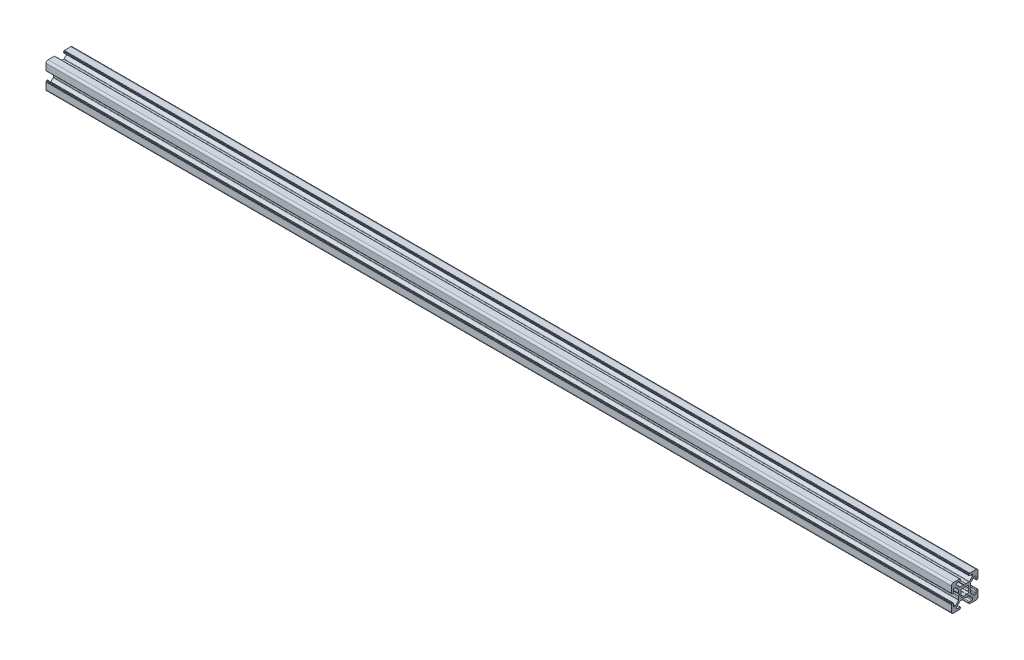
SolidWorks part; units mm, degrees
ref_plane "Front Plane" through (0, 0, 0) normal (0, 0, 1) x (1, 0, 0)
ref_plane "Top Plane" through (0, 0, 0) normal (0, 1, 0) x (1, 0, 0)
ref_plane "Right Plane" through (0, 0, 0) normal (1, 0, 0) x (0, 0, -1)
sketch "Sketch1" plane through (0, 0, 0) normal (0, 0, 1) x (1, 0, 0)
  line L0 (0, 0) -> (680, 0)
  dimension "D1" = 680
other "Metric 2020(1)"
ref_plane "Plane1" through (0, 0, 0) normal (1, 0, 0) x (0, 1, 0)
sketch "Sketch11" plane through (0, 0, 0) normal (1, 0, 0) x (0, 1, 0)
  line L0 (0, 10) -> (0, -10) construction
  line L1 (-10, 0) -> (10, 0) construction
  line L2 (-3.5, 8.5) -> (-5.5, 8.5)
  line L3 (-3.55, 9.7) -> (-3.55, 9.8)
  line L4 (-6, 7.2678) -> (-6, 8)
  line L5 (-7.2678, 6) -> (-8, 6)
  line L6 (-3.75, 10) -> (-8.5, 10)
  line L7 (-9.7, 3.55) -> (-9.8, 3.55)
  line L8 (-9.5, 3.2) -> (-9.5, 3.35)
  line L9 (-9, 3) -> (-9.3, 3)
  line L10 (-4.4732, 0.8536) -> (-4.0381, 0.1)
  line L11 (-4.5, 3.2322) -> (-4.5, 0.9536)
  line L12 (-8.5, 3.5) -> (-8.5, 5.5)
  line L13 (-10, 3.75) -> (-10, 8.5)
  line L14 (-3.5858, 4.6464) -> (-5.8536, 6.9142)
  line L15 (-4.6464, 3.5858) -> (-6.9142, 5.8536)
  line L16 (-3.2, 9.5) -> (-3.35, 9.5)
  line L17 (-3, 9) -> (-3, 9.3)
  line L18 (-0.8536, 4.4732) -> (-0.1, 4.0381)
  line L19 (-3.2322, 4.5) -> (-0.9536, 4.5)
  line L20 (-1.2582, 2.4453) -> (-1.9139, 2.9896)
  line L21 (-2.4453, 1.2582) -> (-2.9922, 1.9099)
  line L22 (3.5, -8.5) -> (5.5, -8.5)
  line L23 (3.55, -9.7) -> (3.55, -9.8)
  line L24 (6, -7.2678) -> (6, -8)
  line L25 (7.2678, -6) -> (8, -6)
  line L26 (3.75, -10) -> (8.5, -10)
  line L27 (9.7, -3.55) -> (9.8, -3.55)
  line L28 (9.5, -3.2) -> (9.5, -3.35)
  line L29 (9, -3) -> (9.3, -3)
  line L30 (4.4732, -0.8536) -> (4.0381, -0.1)
  line L31 (4.5, -3.2322) -> (4.5, -0.9536)
  line L32 (8.5, -3.5) -> (8.5, -5.5)
  line L33 (10, -3.75) -> (10, -8.5)
  line L34 (3.5858, -4.6464) -> (5.8536, -6.9142)
  line L35 (4.6464, -3.5858) -> (6.9142, -5.8536)
  line L36 (3.2, -9.5) -> (3.35, -9.5)
  line L37 (3, -9) -> (3, -9.3)
  line L38 (0.8536, -4.4732) -> (0.1, -4.0381)
  line L39 (3.2322, -4.5) -> (0.9536, -4.5)
  line L40 (1.2582, -2.4453) -> (1.9139, -2.9896)
  line L41 (2.4453, -1.2582) -> (2.9922, -1.9099)
  line L42 (-2.4453, -1.2582) -> (-2.9922, -1.9099)
  line L43 (-1.2582, -2.4453) -> (-1.9139, -2.9896)
  line L44 (-3.2322, -4.5) -> (-0.9536, -4.5)
  line L45 (-0.8536, -4.4732) -> (-0.1, -4.0381)
  line L46 (-3, -9) -> (-3, -9.3)
  line L47 (-3.2, -9.5) -> (-3.35, -9.5)
  line L48 (-4.6464, -3.5858) -> (-6.9142, -5.8536)
  line L49 (-3.5858, -4.6464) -> (-5.8536, -6.9142)
  line L50 (-10, -3.75) -> (-10, -8.5)
  line L51 (-8.5, -3.5) -> (-8.5, -5.5)
  line L52 (-4.5, -3.2322) -> (-4.5, -0.9536)
  line L53 (-4.4732, -0.8536) -> (-4.0381, -0.1)
  line L54 (-9, -3) -> (-9.3, -3)
  line L55 (-9.5, -3.2) -> (-9.5, -3.35)
  line L56 (-9.7, -3.55) -> (-9.8, -3.55)
  line L57 (2.4453, 1.2582) -> (2.9922, 1.9099)
  line L58 (1.2582, 2.4453) -> (1.9139, 2.9896)
  line L59 (3.2322, 4.5) -> (0.9536, 4.5)
  line L60 (0.8536, 4.4732) -> (0.1, 4.0381)
  line L61 (-3.75, -10) -> (-8.5, -10)
  line L62 (-7.2678, -6) -> (-8, -6)
  line L63 (-6, -7.2678) -> (-6, -8)
  line L64 (3, 9) -> (3, 9.3)
  line L65 (3.2, 9.5) -> (3.35, 9.5)
  line L66 (4.6464, 3.5858) -> (6.9142, 5.8536)
  line L67 (3.5858, 4.6464) -> (5.8536, 6.9142)
  line L68 (10, 3.75) -> (10, 8.5)
  line L69 (8.5, 3.5) -> (8.5, 5.5)
  line L70 (4.5, 3.2322) -> (4.5, 0.9536)
  line L71 (4.4732, 0.8536) -> (4.0381, 0.1)
  line L72 (9, 3) -> (9.3, 3)
  line L73 (9.5, 3.2) -> (9.5, 3.35)
  line L74 (9.7, 3.55) -> (9.8, 3.55)
  line L75 (3.75, 10) -> (8.5, 10)
  line L76 (7.2678, 6) -> (8, 6)
  line L77 (6, 7.2678) -> (6, 8)
  line L78 (3.55, 9.7) -> (3.55, 9.8)
  line L79 (3.5, 8.5) -> (5.5, 8.5)
  line L80 (-3.55, -9.7) -> (-3.55, -9.8)
  line L81 (-3.5, -8.5) -> (-5.5, -8.5)
  line L83 (10, -10) -> (-10, -10) construction
  line L84 (10, -10) -> (10, 10) construction
  line L85 (10, 10) -> (-10, 10) construction
  line L86 (-10, -10) -> (-10, 10) construction
  line L87 (10, -10) -> (-10, 10) construction
  line L88 (10, 10) -> (-10, -10) construction
  arc A0 (-10, 8.5) -> (-8.5, 10) centre (-8.5, 8.5) cw
  arc A1 (-8.5, 5.5) -> (-8, 6) centre (-8, 5.5) cw
  arc A2 (-7.2678, 6) -> (-6.9142, 5.8536) centre (-7.2678, 5.5) cw
  arc A3 (-5.8536, 6.9142) -> (-6, 7.2678) centre (-5.5, 7.2678) cw
  arc A4 (-6, 8) -> (-5.5, 8.5) centre (-5.5, 8) cw
  arc A5 (-9.7, 3.55) -> (-9.5, 3.35) centre (-9.7, 3.35) cw
  arc A6 (-9.8, 3.55) -> (-10, 3.75) centre (-9.8, 3.75) cw
  arc A7 (-9.3, 3) -> (-9.5, 3.2) centre (-9.3, 3.2) cw
  arc A8 (-8.5, 3.5) -> (-9, 3) centre (-9, 3.5) cw
  arc A9 (-4.6464, 3.5858) -> (-4.5, 3.2322) centre (-5, 3.2322) cw
  arc A10 (-4.4732, 0.8536) -> (-4.5, 0.9536) centre (-4.3, 0.9536) cw
  arc A11 (-4.0381, 0.1) -> (-4.0381, -0.1) centre (-4.2113, 0) cw
  arc A12 (-3.2, 9.5) -> (-3, 9.3) centre (-3.2, 9.3) cw
  arc A13 (-0.9536, 4.5) -> (-0.8536, 4.4732) centre (-0.9536, 4.3) cw
  arc A14 (-2.9922, 1.9099) -> (-1.9139, 2.9896) centre (0, 0) cw
  arc A15 (-3.2322, 4.5) -> (-3.5858, 4.6464) centre (-3.2322, 5) cw
  arc A16 (-3.75, 10) -> (-3.55, 9.8) centre (-3.75, 9.8) cw
  arc A17 (-3.35, 9.5) -> (-3.55, 9.7) centre (-3.35, 9.7) cw
  arc A18 (2.4453, -1.2582) -> (2.4453, 1.2582) centre (0, 0) ccw
  arc A19 (-3, 9) -> (-3.5, 8.5) centre (-3.5, 9) cw
  arc A20 (-2.4453, -1.2582) -> (-2.4453, 1.2582) centre (0, 0) cw
  arc A21 (10, -8.5) -> (8.5, -10) centre (8.5, -8.5) cw
  arc A22 (8.5, -5.5) -> (8, -6) centre (8, -5.5) cw
  arc A23 (7.2678, -6) -> (6.9142, -5.8536) centre (7.2678, -5.5) cw
  arc A24 (5.8536, -6.9142) -> (6, -7.2678) centre (5.5, -7.2678) cw
  arc A25 (6, -8) -> (5.5, -8.5) centre (5.5, -8) cw
  arc A26 (9.7, -3.55) -> (9.5, -3.35) centre (9.7, -3.35) cw
  arc A27 (9.8, -3.55) -> (10, -3.75) centre (9.8, -3.75) cw
  arc A28 (9.3, -3) -> (9.5, -3.2) centre (9.3, -3.2) cw
  arc A29 (8.5, -3.5) -> (9, -3) centre (9, -3.5) cw
  arc A30 (4.6464, -3.5858) -> (4.5, -3.2322) centre (5, -3.2322) cw
  arc A31 (4.4732, -0.8536) -> (4.5, -0.9536) centre (4.3, -0.9536) cw
  arc A32 (3.2, -9.5) -> (3, -9.3) centre (3.2, -9.3) cw
  arc A33 (-0.1, -4.0381) -> (0.1, -4.0381) centre (0, -4.2113) cw
  arc A34 (0.9536, -4.5) -> (0.8536, -4.4732) centre (0.9536, -4.3) cw
  arc A35 (2.9922, -1.9099) -> (1.9139, -2.9896) centre (0, 0) cw
  arc A36 (1.2582, -2.4453) -> (-1.2582, -2.4453) centre (0, 0) cw
  arc A37 (3.2322, -4.5) -> (3.5858, -4.6464) centre (3.2322, -5) cw
  arc A38 (3.75, -10) -> (3.55, -9.8) centre (3.75, -9.8) cw
  arc A39 (3.35, -9.5) -> (3.55, -9.7) centre (3.35, -9.7) cw
  arc A40 (3, -9) -> (3.5, -8.5) centre (3.5, -9) cw
  arc A41 (-3, -9) -> (-3.5, -8.5) centre (-3.5, -9) ccw
  arc A42 (-3.35, -9.5) -> (-3.55, -9.7) centre (-3.35, -9.7) ccw
  arc A43 (-3.75, -10) -> (-3.55, -9.8) centre (-3.75, -9.8) ccw
  arc A44 (-3.2322, -4.5) -> (-3.5858, -4.6464) centre (-3.2322, -5) ccw
  arc A45 (-2.9922, -1.9099) -> (-1.9139, -2.9896) centre (0, 0) ccw
  arc A46 (-0.9536, -4.5) -> (-0.8536, -4.4732) centre (-0.9536, -4.3) ccw
  arc A47 (-3.2, -9.5) -> (-3, -9.3) centre (-3.2, -9.3) ccw
  arc A48 (-4.4732, -0.8536) -> (-4.5, -0.9536) centre (-4.3, -0.9536) ccw
  arc A49 (3, 9) -> (3.5, 8.5) centre (3.5, 9) ccw
  arc A50 (3.35, 9.5) -> (3.55, 9.7) centre (3.35, 9.7) ccw
  arc A51 (3.75, 10) -> (3.55, 9.8) centre (3.75, 9.8) ccw
  arc A52 (3.2322, 4.5) -> (3.5858, 4.6464) centre (3.2322, 5) ccw
  arc A53 (1.2582, 2.4453) -> (-1.2582, 2.4453) centre (0, 0) ccw
  arc A54 (-4.6464, -3.5858) -> (-4.5, -3.2322) centre (-5, -3.2322) ccw
  arc A55 (-8.5, -3.5) -> (-9, -3) centre (-9, -3.5) ccw
  arc A56 (-9.3, -3) -> (-9.5, -3.2) centre (-9.3, -3.2) ccw
  arc A57 (-9.8, -3.55) -> (-10, -3.75) centre (-9.8, -3.75) ccw
  arc A58 (-9.7, -3.55) -> (-9.5, -3.35) centre (-9.7, -3.35) ccw
  arc A59 (-6, -8) -> (-5.5, -8.5) centre (-5.5, -8) ccw
  arc A60 (2.9922, 1.9099) -> (1.9139, 2.9896) centre (0, 0) ccw
  arc A61 (0.9536, 4.5) -> (0.8536, 4.4732) centre (0.9536, 4.3) ccw
  arc A62 (-0.1, 4.0381) -> (0.1, 4.0381) centre (0, 4.2113) ccw
  arc A63 (-5.8536, -6.9142) -> (-6, -7.2678) centre (-5.5, -7.2678) ccw
  arc A64 (-7.2678, -6) -> (-6.9142, -5.8536) centre (-7.2678, -5.5) ccw
  arc A65 (-8.5, -5.5) -> (-8, -6) centre (-8, -5.5) ccw
  arc A66 (-10, -8.5) -> (-8.5, -10) centre (-8.5, -8.5) ccw
  arc A67 (3.2, 9.5) -> (3, 9.3) centre (3.2, 9.3) ccw
  arc A68 (4.0381, 0.1) -> (4.0381, -0.1) centre (4.2113, 0) ccw
  arc A69 (4.4732, 0.8536) -> (4.5, 0.9536) centre (4.3, 0.9536) ccw
  arc A70 (4.6464, 3.5858) -> (4.5, 3.2322) centre (5, 3.2322) ccw
  arc A71 (8.5, 3.5) -> (9, 3) centre (9, 3.5) ccw
  arc A72 (9.3, 3) -> (9.5, 3.2) centre (9.3, 3.2) ccw
  arc A73 (9.8, 3.55) -> (10, 3.75) centre (9.8, 3.75) ccw
  arc A74 (9.7, 3.55) -> (9.5, 3.35) centre (9.7, 3.35) ccw
  arc A75 (6, 8) -> (5.5, 8.5) centre (5.5, 8) ccw
  arc A76 (5.8536, 6.9142) -> (6, 7.2678) centre (5.5, 7.2678) ccw
  arc A77 (7.2678, 6) -> (6.9142, 5.8536) centre (7.2678, 5.5) ccw
  arc A78 (8.5, 5.5) -> (8, 6) centre (8, 5.5) ccw
  arc A79 (10, 8.5) -> (8.5, 10) centre (8.5, 8.5) ccw
  point P241 (0, 0)
  dimension "D4" = 5.5
  dimension "D1" = 6
  dimension "D2" = 20
  dimension "D3" = 20
  dimension "D5" = 5.5
  dimension "D6" = 10
  dimension "D7" = 6
  dimension "D8" = 6
  dimension "D9" = 6
